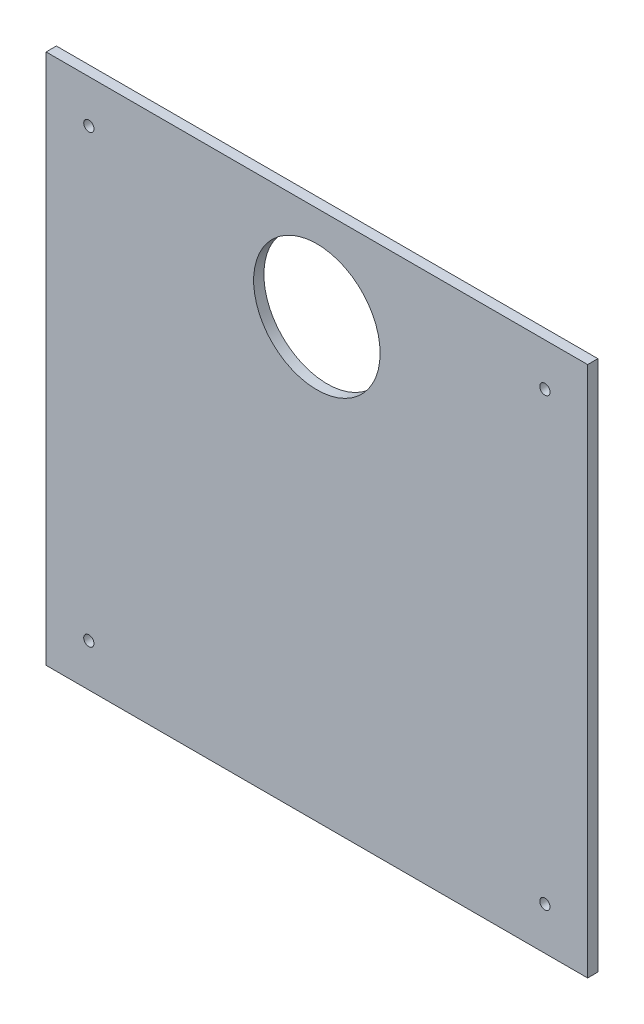
SolidWorks part; units mm, degrees
material "Acrylic (Medium-high impact)"
ref_plane "Front Plane" through (0, 0, 0) normal (0, 0, 1) x (1, 0, 0)
ref_plane "Top Plane" through (0, 0, 0) normal (0, 1, 0) x (1, 0, 0)
ref_plane "Right Plane" through (0, 0, 0) normal (1, 0, 0) x (0, 0, -1)
sketch "Sketch1" plane through (0, 0, 0) normal (0, 0, 1) x (1, 0, 0)
  line L1 (158.4, -228.6) -> (-158.4, -228.6)
  line L2 (158.4, -228.6) -> (158.4, 228.6)
  line L3 (158.4, 228.6) -> (-158.4, 228.6)
  line L4 (-158.4, -228.6) -> (-158.4, 228.6)
  line L5 (158.4, -228.6) -> (-158.4, 228.6) construction
  line L6 (158.4, 228.6) -> (-158.4, -228.6) construction
  point P0 (0, 0)
  dimension "D1" = 457.2
  dimension "D2" = 316.8
extrude "Boss-Extrude1" add sketch "Sketch1" along normal blind 6
sketch "Sketch2" plane through (0, 0, 6) normal (0, 0, 1) x (1, 0, 0)
  line L0 (-158.4, 173.6) -> (158.4, 173.6) construction
  line L1 (-158.4, 228.6) -> (-158.4, -228.6) construction
  line L2 (158.4, -228.6) -> (158.4, 228.6) construction
  line L3 (158.4, 228.6) -> (-158.4, 228.6) construction
  circle A0 centre (0, 173.6) radius 37
  dimension "D2" = 74
  dimension "D1" = 55
extrude "Cut-Extrude1" cut sketch "Sketch2" against normal through all
sketch "Sketch3" plane through (0, 0, 6) normal (0, 0, 1) x (1, 0, 0)
  line L0 (-158.4, -82.2) -> (158.4, -82.2)
  line L1 (-158.4, 228.6) -> (-158.4, -228.6) construction
  line L2 (158.4, -228.6) -> (158.4, 228.6) construction
  line L3 (158.4, -82.2) -> (158.4, -228.6)
  line L4 (158.4, -228.6) -> (-158.4, -228.6)
  line L5 (-158.4, -228.6) -> (-158.4, -82.2)
  dimension "D1" = 146.4
extrude "Cut-Extrude2" cut sketch "Sketch3" against normal through all
sketch "Sketch4" plane through (0, 0, 6) normal (0, 0, 1) x (1, 0, 0)
  line L0 (-148.4, -72.2) -> (-148.4, 218.6) construction
  line L1 (-148.4, 218.6) -> (148.4, 218.6) construction
  line L2 (148.4, 218.6) -> (148.4, -72.2) construction
  line L3 (148.4, -72.2) -> (-148.4, -72.2) construction
  line L4 (158.4, 228.6) -> (-158.4, 228.6) construction
  line L5 (158.4, -82.2) -> (158.4, 228.6) construction
  line L6 (158.4, -82.2) -> (-158.4, -82.2) construction
  line L7 (-158.4, 228.6) -> (-158.4, -82.2) construction
  circle A0 centre (-133.4, 203.6) radius 3
  circle A1 centre (-133.4, -57.2) radius 3
  circle A2 centre (133.4, -57.2) radius 3
  circle A3 centre (133.4, 203.6) radius 3
  point P20 (0, 0)
  point P21 (0, 0)
  point P22 (0, 0)
  point P23 (0, 0)
  dimension "D5" = 15
  dimension "D7" = 6
  dimension "D10" = 6
  dimension "D11" = 6
  dimension "D12" = 6
  dimension "D1" = 10
  dimension "D2" = 10
  dimension "D3" = 10
  dimension "D4" = 10
  dimension "D6" = 15
  dimension "D8" = 15
  dimension "D9" = 15
extrude "Cut-Extrude3" cut sketch "Sketch4" against normal through all
